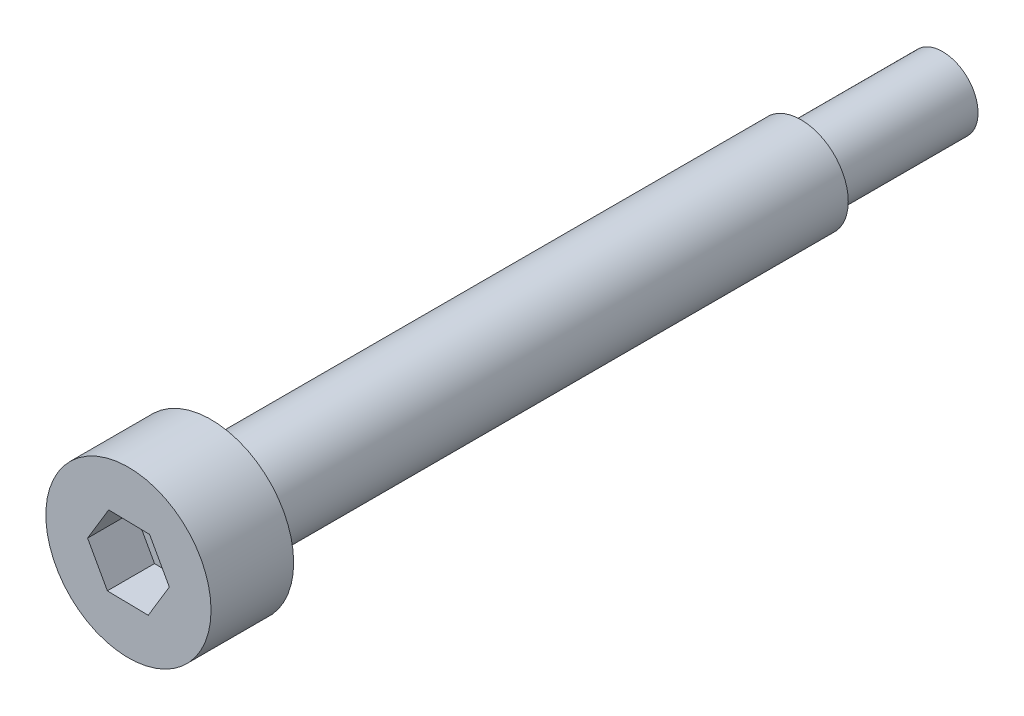
SolidWorks part; units mm, degrees
material "AISI 304"
ref_plane "前视基准面" through (0, 0, 0) normal (0, 0, 1) x (1, 0, 0)
ref_plane "上视基准面" through (0, 0, 0) normal (0, 1, 0) x (1, 0, 0)
ref_plane "右视基准面" through (0, 0, 0) normal (1, 0, 0) x (0, 0, -1)
sketch "草图1" plane through (0, 0, 0) normal (0, 0, 1) x (1, 0, 0)
  circle A0 centre (0, 0) radius 3.5
  dimension "D1" = 7
extrude "凸台-拉伸1" add sketch "草图1" along normal blind 3.5
sketch "草图2" plane through (0, 0, 3.5) normal (0, 0, 1) x (1, 0, 0)
  line L1 (0.8936, 1.4837) -> (-0.8381, 1.5158)
  line L2 (-0.8381, 1.5158) -> (-1.7318, 0.0321)
  line L3 (-1.7318, 0.0321) -> (-0.8936, -1.4837)
  line L4 (-0.8936, -1.4837) -> (0.8381, -1.5158)
  line L5 (0.8381, -1.5158) -> (1.7318, -0.0321)
  line L6 (1.7318, -0.0321) -> (0.8936, 1.4837)
  circle A0 centre (0, 0) radius 1.5 construction
  dimension "D1" = 3
extrude "切除-拉伸1" cut sketch "草图2" against normal blind 2
sketch "草图3" plane through (0, 0, 0) normal (0, 0, -1) x (-1, 0, 0)
  circle A0 centre (0, 0) radius 2
  dimension "D1" = 4
extrude "凸台-拉伸2" add sketch "草图3" along normal blind 25
sketch "草图4" plane through (0, 0, -25) normal (0, 0, -1) x (-1, 0, 0)
  circle A0 centre (0, 0) radius 1.5
  dimension "D1" = 3
extrude "凸台-拉伸3" add sketch "草图4" along normal blind 6
cosmetic thread "装饰螺纹线1" parameters "D2"=2
